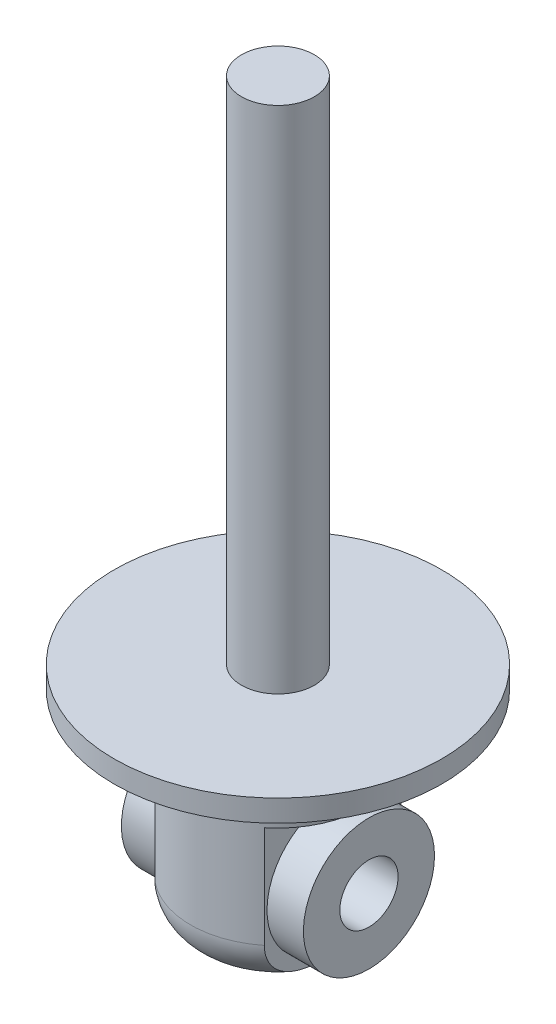
SolidWorks part; units mm, degrees
ref_plane "Front Plane" through (0, 0, 0) normal (0, 0, 1) x (1, 0, 0)
ref_plane "Top Plane" through (0, 0, 0) normal (0, 1, 0) x (1, 0, 0)
ref_plane "Right Plane" through (0, 0, 0) normal (1, 0, 0) x (0, 0, -1)
sketch "Sketch1" plane through (0, 0, 0) normal (0, 1, 0) x (1, 0, 0)
  circle A0 centre (0, 0) radius 22.5
  dimension "D1" = 45
extrude "Boss-Extrude1" add sketch "Sketch1" along normal blind 3
sketch "Sketch2" plane through (0, 3, 0) normal (0, 1, 0) x (1, 0, 0)
  circle A0 centre (0, 0) radius 5
  circle A1 centre (0, 0) radius 22.5 construction
  dimension "D1" = 10
extrude "Boss-Extrude2" add sketch "Sketch2" along normal blind 70
sketch "Sketch3" plane through (0, 0, 0) normal (0, -1, 0) x (1, 0, 0)
  circle A0 centre (0, 0) radius 12
  dimension "D1" = 24
extrude "Boss-Extrude3" add sketch "Sketch3" along normal blind 28
fillet "Fillet2" radius 6 1 edges at (0, -28, -12)
sketch "Sketch8" plane through (0, 0, 0) normal (0, 0, 1) x (1, 0, 0)
  line L0 (0, 0) -> (0, -28) construction
  line L1 (-6, -28) -> (6, -28) construction
  line L2 (7.5, -8) -> (7.5, -28)
  line L3 (7.5, -28) -> (19.7638, -28)
  line L4 (19.7638, -28) -> (19.7638, -8)
  line L5 (19.7638, -8) -> (7.5, -8)
  line L6 (-19.7638, -28) -> (-19.7638, -8)
  line L7 (-7.5, -28) -> (-19.7638, -28)
  line L8 (-7.5, -8) -> (-7.5, -28)
  line L9 (-19.7638, -8) -> (-7.5, -8)
  dimension "D1" = 15
  dimension "D2" = 20
extrude "Cut-Extrude4" cut sketch "Sketch8" against normal through all both and the other way through all
sketch "Sketch11" plane through (0, 0, 0) normal (1, 0, 0) x (0, 0, -1)
  line L0 (0, 0) -> (0, -28) construction
  line L1 (-6, -28) -> (6, -28) construction
  circle A0 centre (0, -18) radius 4
  dimension "D1" = 8
  dimension "D2" = 10
extrude "Cut-Extrude6" cut sketch "Sketch11" against normal through all both and the other way through all
sketch "Sketch14" plane through (0, 0, 0) normal (1, 0, 0) x (0, 0, -1)
  circle A0 centre (0, -18) radius 9
  circle A1 centre (0, -18) radius 4 construction
  circle A2 centre (0, -18) radius 4
  dimension "D1" = 18
extrude "Boss-Extrude8" add sketch "Sketch14" along normal mid plane 25
